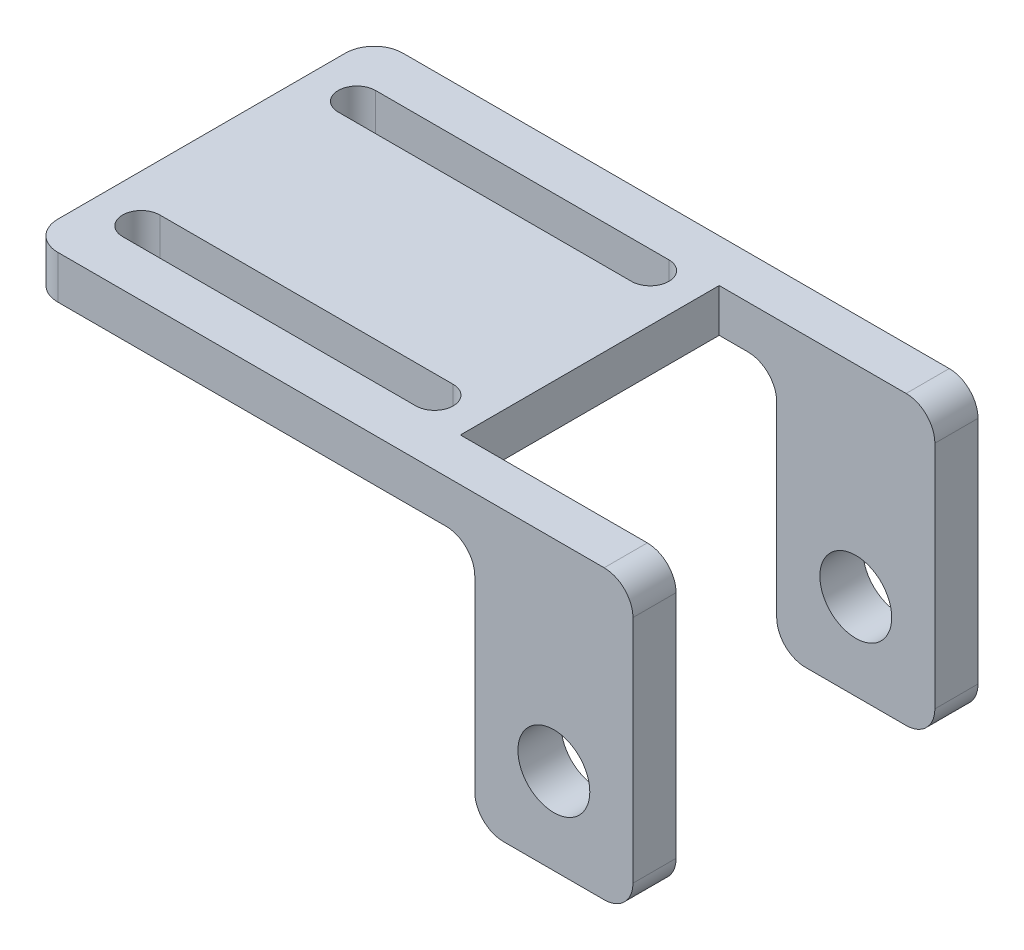
SolidWorks part; units mm, degrees
material "ABS"
ref_plane "Front Plane" through (0, 0, 0) normal (0, 0, 1) x (1, 0, 0)
ref_plane "Top Plane" through (0, 0, 0) normal (0, 1, 0) x (1, 0, 0)
ref_plane "Right Plane" through (0, 0, 0) normal (1, 0, 0) x (0, 0, -1)
sketch "Sketch1" plane through (0, 0, 0) normal (0, 1, 0) x (1, 0, 0)
  line L1 (0, 0) -> (42, 0)
  line L2 (0, 0) -> (0, 24)
  line L3 (0, 24) -> (42, 24)
  line L4 (42, 0) -> (42, 24)
  dimension "D1" = 24
  dimension "D2" = 42
extrude "Boss-Extrude1" add sketch "Sketch1" along normal blind 3
sketch "Sketch2" plane through (0, 0, 0) normal (0, -1, 0) x (1, 0, 0)
  line L1 (42, 0) -> (31, 0)
  line L2 (42, 0) -> (42, -3)
  line L3 (42, -3) -> (31, -3)
  line L4 (31, 0) -> (31, -3)
  line L5 (42, -24) -> (31, -24)
  line L6 (42, -24) -> (42, -21)
  line L7 (42, -21) -> (31, -21)
  line L8 (31, -24) -> (31, -21)
  dimension "D1" = 3
  dimension "D2" = 3
  dimension "D3" = 11
  dimension "D4" = 11
extrude "Boss-Extrude2" add sketch "Sketch2" along normal blind 17
sketch "Sketch3" plane through (0, 0, 0) normal (0, 0, 1) x (1, 0, 0)
  line L0 (0, 3) -> (42, 3) construction
  line L4 (36.5, 3) -> (36.5, -17) construction
  line L5 (42, -17) -> (31, -17) construction
  circle A0 centre (36.5, -11) radius 2.5
  dimension "D1" = 5
  dimension "D2" = 6
extrude "Cut-Extrude1" cut sketch "Sketch3" against normal through all
sketch "Sketch4" plane through (0, 3, 0) normal (0, 1, 0) x (1, 0, 0)
  line L0 (42, 0) -> (42, 24) construction
  line L1 (42, 21) -> (27, 21)
  line L2 (42, 21) -> (42, 3)
  line L3 (42, 3) -> (27, 3)
  line L4 (27, 21) -> (27, 3)
  line L5 (42, 24) -> (0, 24) construction
  line L6 (0, 0) -> (42, 0) construction
  dimension "D1" = 3
  dimension "D2" = 3
  dimension "D3" = 15
extrude "Cut-Extrude2" cut sketch "Sketch4" against normal blind 3
fillet "Fillet1" radius 2 2 edges at (0, 1.5, -24) (0, 1.5, 0)
fillet "Fillet2" radius 2 6 edges at (42, 3, -1.5) (42, -17, -1.5) (31, -17, -1.5) (42, -17, -22.5) (31, -17, -22.5) (42, 3, -22.5)
fillet "Fillet3" radius 2 2 edges at (31, 0, -1.5) (31, 0, -22.5)
sketch "Sketch6" plane through (0, 3, 0) normal (0, 1, 0) x (1, 0, 0)
  line L0 (27, 19.5) -> (0, 19.5) construction
  line L1 (27, 21) -> (27, 3) construction
  line L2 (0, 22) -> (0, 2) construction
  line L3 (27, 4.5) -> (0, 4.5) construction
  line L4 (3.3, 19.5) -> (23.7, 19.5) construction
  line L5 (3.3, 20.8) -> (23.7, 20.8)
  line L6 (3.3, 18.2) -> (23.7, 18.2)
  line L7 (3.3, 4.5) -> (23.7, 4.5) construction
  line L8 (3.3, 5.8) -> (23.7, 5.8)
  line L9 (3.3, 3.2) -> (23.7, 3.2)
  line L10 (0, 12) -> (27, 12) construction
  arc A0 (3.3, 20.8) -> (3.3, 18.2) centre (3.3, 19.5) ccw
  arc A1 (23.7, 18.2) -> (23.7, 20.8) centre (23.7, 19.5) ccw
  arc A2 (3.3, 5.8) -> (3.3, 3.2) centre (3.3, 4.5) ccw
  arc A3 (23.7, 3.2) -> (23.7, 5.8) centre (23.7, 4.5) ccw
  point P12 (13.5, 19.5)
  point P17 (13.5, 4.5)
  point P24 (25, 4.5)
  point P25 (25, 19.5)
  point P26 (2, 4.5)
  point P27 (2, 19.5)
  dimension "D1" = 1.5
  dimension "D2" = 1.5
  dimension "D3" = 2.6
  dimension "D4" = 2.6
  dimension "D5" = 2
  dimension "D6" = 2
  dimension "D7" = 2
  dimension "D8" = 2
  dimension "D9" = 7.5
extrude "Cut-Extrude3" cut sketch "Sketch6" against normal through all
sketch "Sketch5" plane through (0, 3, 0) normal (0, 1, 0) x (1, 0, 0)
  line L0 (0, 12) -> (27, 12) construction
  line L1 (0, 22) -> (0, 2) construction
  line L2 (27, 21) -> (27, 3) construction
sketch "Sketch7" plane through (0, 0, 0) normal (0, -1, 0) x (1, 0, 0)
  line L0 (0, -12) -> (27, -12) construction
